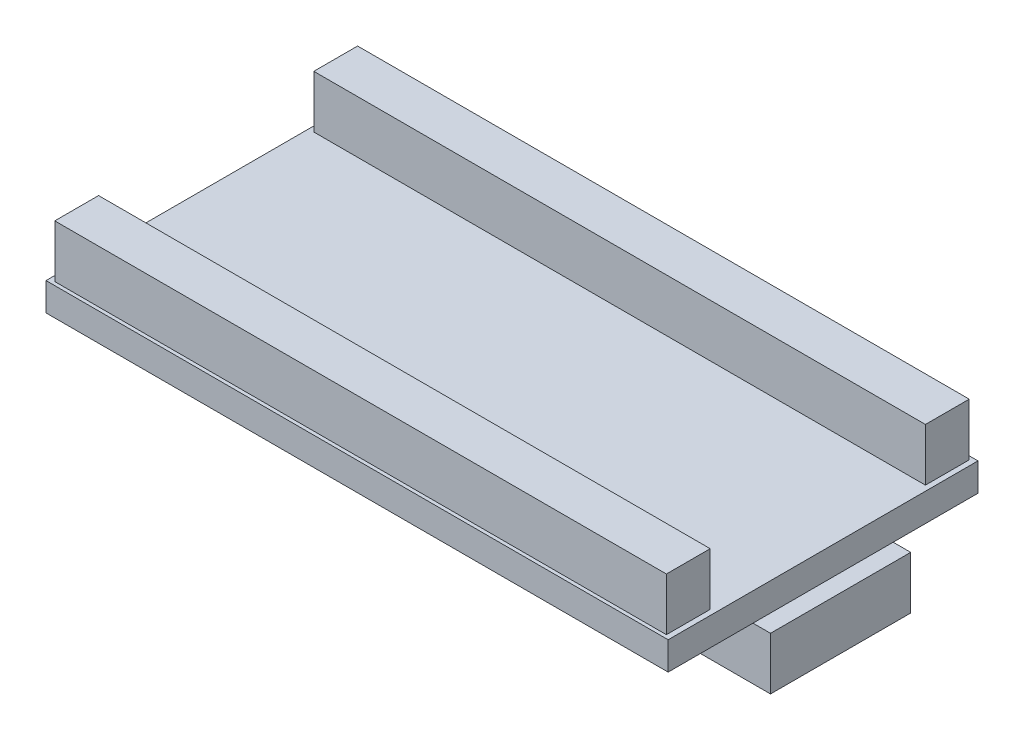
SolidWorks part; units mm, degrees
ref_plane "Front Plane" through (0, 0, 0) normal (0, 0, 1) x (1, 0, 0)
ref_plane "Top Plane" through (0, 0, 0) normal (0, 1, 0) x (1, 0, 0)
ref_plane "Right Plane" through (0, 0, 0) normal (1, 0, 0) x (0, 0, -1)
sketch "Sketch1" plane through (0, 0, 0) normal (0, 1, 0) x (1, 0, 0)
  line L1 (-17.75, 8.84) -> (17.75, 8.84)
  line L2 (-17.75, 8.84) -> (-17.75, -8.84)
  line L3 (-17.75, -8.84) -> (17.75, -8.84)
  line L4 (17.75, 8.84) -> (17.75, -8.84)
  line L5 (-17.75, 8.84) -> (17.75, -8.84) construction
  line L6 (-17.75, -8.84) -> (17.75, 8.84) construction
  point P0 (0, 0)
  dimension "D1" = 35.5
  dimension "D2" = 17.68
extrude "Boss-Extrude1" add sketch "Sketch1" along normal blind 1.6
sketch "Sketch2" plane through (0, 1.6, 0) normal (0, 1, 0) x (1, 0, 0)
  line L0 (-17.75, -8.84) -> (17.75, -8.84) construction
  line L1 (-17.45, 8.64) -> (17.45, 8.64)
  line L2 (-17.45, 8.64) -> (-17.45, 6.14)
  line L3 (-17.45, 6.14) -> (17.45, 6.14)
  line L4 (17.45, 8.64) -> (17.45, 6.14)
  line L5 (17.45, -8.64) -> (-17.45, -8.64)
  line L6 (17.45, -8.64) -> (17.45, -6.14)
  line L7 (17.45, -6.14) -> (-17.45, -6.14)
  line L8 (-17.45, -8.64) -> (-17.45, -6.14)
  line L9 (17.75, 8.84) -> (-17.75, 8.84) construction
  line L10 (-17.75, 8.84) -> (-17.75, -8.84) construction
  line L11 (17.75, -8.84) -> (17.75, 8.84) construction
  dimension "D1" = 2.5
  dimension "D2" = 2.5
  dimension "D3" = 0.2
  dimension "D4" = 0.2
  dimension "D5" = 0.3
  dimension "D6" = 0.3
  dimension "D7" = 0.3
  dimension "D8" = 0.3
extrude "Boss-Extrude2" add sketch "Sketch2" along normal blind 3
sketch "Sketch3" plane through (0, 0, 0) normal (0, -1, 0) x (1, 0, 0)
  line L0 (17.75, 8.84) -> (17.75, -8.84) construction
  line L1 (13.15, 4) -> (18.75, 4)
  line L2 (13.15, 4) -> (13.15, -4)
  line L3 (13.15, -4) -> (18.75, -4)
  line L4 (18.75, 4) -> (18.75, -4)
  line L5 (-17.75, 8.84) -> (17.75, 8.84) construction
  dimension "D1" = 8
  dimension "D2" = 5.6
  dimension "D3" = 1
  dimension "D4" = 4.84
extrude "Boss-Extrude3" add sketch "Sketch3" along normal blind 3
